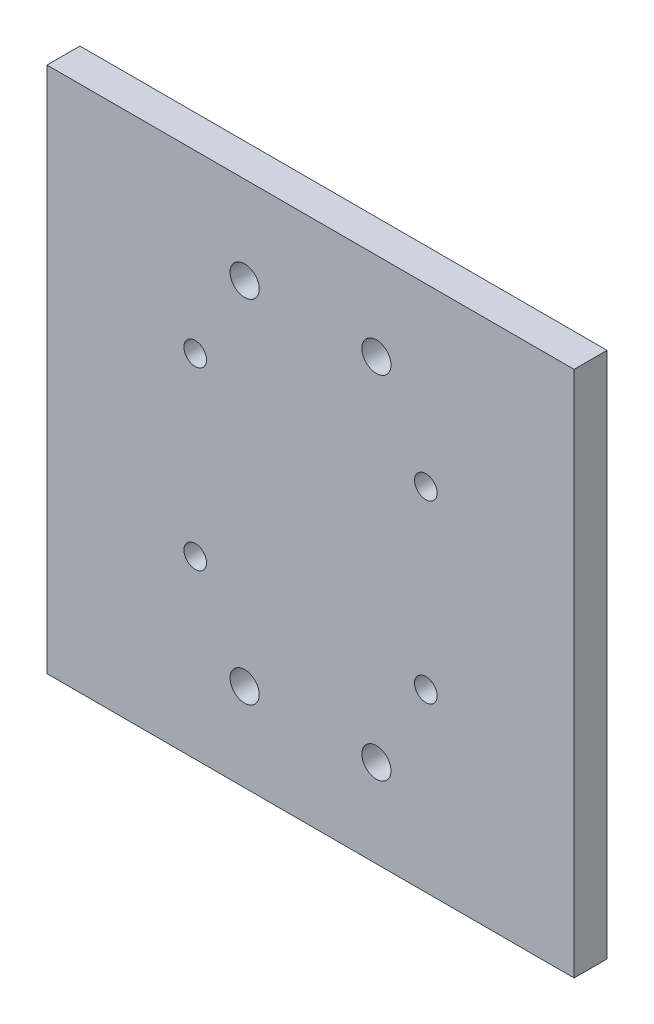
SolidWorks part; units mm, degrees
ref_plane "Front Plane" through (0, 0, 0) normal (0, 0, 1) x (1, 0, 0)
ref_plane "Top Plane" through (0, 0, 0) normal (0, 1, 0) x (1, 0, 0)
ref_plane "Right Plane" through (0, 0, 0) normal (1, 0, 0) x (0, 0, -1)
sketch "Sketch1" plane through (0, 0, 0) normal (0, 0, 1) x (1, 0, 0)
  line L1 (0, 0) -> (152.4, 0)
  line L2 (0, 0) -> (0, 152.4)
  line L3 (0, 152.4) -> (152.4, 152.4)
  line L4 (152.4, 0) -> (152.4, 152.4)
  dimension "D1" = 152.4
  dimension "D2" = 152.4
extrude "Boss-Extrude1" add sketch "Sketch1" along normal blind 9.525
hole_wizard "5/16-18 Tapped Hole1" positions "Sketch2" profile "Sketch3" tap size "5/16-18" standard "ANSI Inch" end condition through all
sketch "Sketch2" plane through (0, 0, 9.525) normal (0, 0, 1) x (1, 0, 0)
  line L0 (76.2, 152.4) -> (76.2, 0) construction
  line L1 (152.4, 152.4) -> (0, 152.4) construction
  line L2 (0, 0) -> (152.4, 0) construction
  point P0 (109.5375, 101.6)
  point P2 (42.8625, 101.6)
  point P4 (109.5375, 50.8)
  point P6 (42.8625, 50.8)
  point P19 (0, 0)
  point P20 (0, 0)
  dimension "D1" = 66.675
  dimension "D2" = 66.675
  dimension "D3" = 50.8
  dimension "D4" = 50.8
sketch "Sketch3" plane through (109.5375, 101.6, 9.525) normal (1, 0, 0) x (0, -1, 0)
  line L0 (0, 0) -> (0, 9.525)
  line L1 (0, 9.525) -> (3.2639, 9.525)
  line L2 (3.2639, 9.525) -> (3.2639, 0)
  line L5 (3.2639, 0) -> (0, 0)
  line L11 (0, -6.35) -> (0, 107.95) construction
  dimension "Thru Tap Drill Dia." = 6.5278
  dimension "Thru Tap Drill Depth" = 9.525
cosmetic thread "Hole Thread1" parameters "D2"=7.9375
cosmetic thread "Hole Thread2" parameters "D2"=7.9375
cosmetic thread "Hole Thread3" parameters "D2"=7.9375
cosmetic thread "Hole Thread4" parameters "D2"=7.9375
hole_wizard "5/16 Clearance Hole1" positions "Sketch4" profile "Sketch5" hole size "5/16" standard "ANSI Inch" end condition through all
sketch "Sketch4" plane through (0, 0, 9.525) normal (0, 0, 1) x (1, 0, 0)
  line L0 (76.2, 152.4) -> (76.2, 0) construction
  line L1 (152.4, 152.4) -> (0, 152.4) construction
  line L2 (0, 0) -> (152.4, 0) construction
  line L5 (152.4, 76.2) -> (0, 76.2) construction
  line L6 (152.4, 0) -> (152.4, 152.4) construction
  line L7 (0, 152.4) -> (0, 0) construction
  point P0 (95.25, 127)
  point P2 (57.15, 127)
  point P24 (0, 0)
  point P25 (95.25, 25.4)
  point P26 (57.15, 25.4)
  dimension "D1" = 38.1
  dimension "D2" = 25.4
sketch "Sketch5" plane through (95.25, 127, 9.525) normal (1, 0, 0) x (0, -1, 0)
  line L0 (0, 0) -> (0, 9.525)
  line L1 (0, 9.525) -> (4.2164, 9.525)
  line L2 (4.2164, 9.525) -> (4.2164, 0)
  line L5 (4.2164, 0) -> (0, 0)
  line L11 (0, -6.35) -> (0, 107.95) construction
  dimension "Thru Hole Dia." = 8.4328
  dimension "Thru Hole Depth" = 9.525
